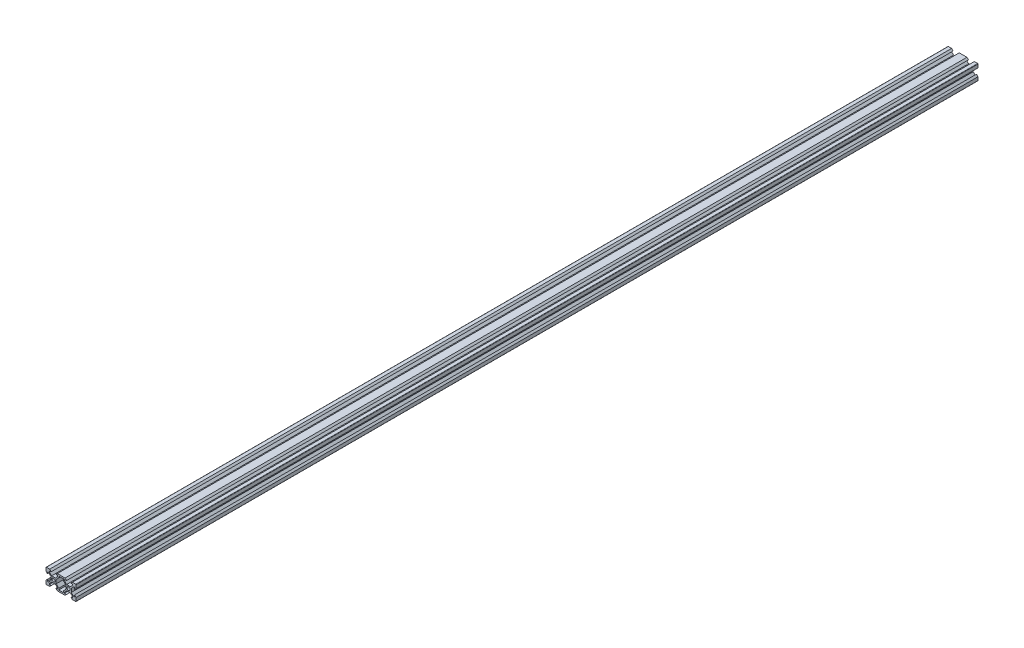
SolidWorks part; units mm, degrees
material "6063-T5"
ref_plane "Front Plane" through (0, 0, 0) normal (0, 0, 1) x (1, 0, 0)
ref_plane "Top Plane" through (0, 0, 0) normal (0, 1, 0) x (1, 0, 0)
ref_plane "Right Plane" through (0, 0, 0) normal (1, 0, 0) x (0, 0, -1)
sketch "Sketch1" plane through (0, 0, 0) normal (0, 0, 1) x (1, 0, 0)
  line L0 (-26.1395, 0) -> (11.0607, 0) construction
  line L1 (0, -20.0817) -> (0, 17.1243) construction
  line L2 (-20, 10.7318) -> (-20, -11.6858) construction
  line L3 (20, 11.8444) -> (20, -11.2237) construction
  line L4 (-23.1467, 10) -> (24.2381, 10) construction
  line L5 (23.8217, -10) -> (-26.7834, -10) construction
  line L6 (3, -5.9393) -> (3, -8)
  line L7 (-20, -10) -> (-15.5, -10)
  line L8 (-20, -10) -> (-20, -5.5)
  line L9 (-18, -5.5) -> (-16.5607, -5.5)
  line L10 (-15.5, -8) -> (-15.5, -6.5607)
  line L11 (-20, 10) -> (-15.5, 10)
  line L12 (-20, 10) -> (-20, 5.5)
  line L13 (-18, 5.5) -> (-16.5607, 5.5)
  line L14 (-15.5, 8) -> (-15.5, 6.5607)
  line L15 (20, 10) -> (15.5, 10)
  line L16 (20, 10) -> (20, 5.5)
  line L17 (18, 5.5) -> (16.5607, 5.5)
  line L18 (15.5, 8) -> (15.5, 6.5607)
  line L19 (20, -10) -> (15.5, -10)
  line L20 (20, -10) -> (20, -5.5)
  line L21 (18, -5.5) -> (16.5607, -5.5)
  line L22 (15.5, -8) -> (15.5, -6.5607)
  line L23 (4.5, -6.5607) -> (4.5, -8)
  line L24 (12.5393, 3.6) -> (15.5, 6.5607)
  line L25 (7.4607, -3.6) -> (4.5, -6.5607)
  line L27 (-4.5, 8) -> (-6.9, 8)
  line L28 (-12.5393, -3.6) -> (-15.5, -6.5607)
  line L29 (7.4607, 3.6) -> (4.5, 6.5607)
  line L30 (12.5393, -3.6) -> (15.5, -6.5607)
  line L31 (-13.6, -2.5393) -> (-16.5607, -5.5)
  line L32 (-13.6, 2.5393) -> (-16.5607, 5.5)
  line L33 (6.4, -2.5393) -> (3, -5.9393)
  line L34 (20, 5.5) -> (20, 5.1)
  line L35 (20, 5.1) -> (18, 3.1)
  line L36 (18, 3.1) -> (18, 5.5)
  line L37 (20, -5.5) -> (20, -5.1)
  line L38 (20, -5.1) -> (18, -3.1)
  line L39 (18, -3.1) -> (18, -5.5)
  line L40 (15.5, 10) -> (15.1, 10)
  line L41 (15.1, 10) -> (13.1, 8)
  line L42 (13.1, 8) -> (15.5, 8)
  line L43 (15.5, -10) -> (15.1, -10)
  line L44 (15.1, -10) -> (13.5138, -8)
  line L45 (13.5138, -8) -> (15.5, -8)
  line L46 (-15.5, 10) -> (-15.1, 10)
  line L47 (-15.1, 10) -> (-13.1, 8)
  line L48 (-13.1, 8) -> (-15.5, 8)
  line L49 (-20, 5.5) -> (-20, 5.1)
  line L50 (-20, 5.1) -> (-18, 3.1)
  line L51 (-18, 3.1) -> (-18, 5.5)
  line L52 (-20, -5.5) -> (-20, -5.1)
  line L53 (-20, -5.1) -> (-18, -3.1)
  line L54 (-18, -3.1) -> (-18, -5.5)
  line L55 (-15.5, -10) -> (-15.1, -10)
  line L56 (-15.1, -10) -> (-13.1, -8)
  line L57 (-13.1, -8) -> (-15.5, -8)
  line L58 (6.4, 2.5393) -> (3, 5.9393)
  line L59 (3, 8) -> (-3, 8)
  line L61 (-3, 5.9393) -> (-3, 8)
  line L62 (-12.5393, 3.6) -> (-15.5, 6.5607)
  line L63 (-4.5, 6.5607) -> (-4.5, 8)
  line L64 (4.5, 6.5607) -> (4.5, 8)
  line L65 (3, 5.9393) -> (3, 8)
  line L66 (13.6, 2.5393) -> (16.5607, 5.5)
  line L67 (12.1, 0) -> (30.0509, 0) construction
  line L68 (-7.4607, 3.6) -> (-4.5, 6.5607)
  line L69 (3, -8) -> (-3, -8)
  line L70 (-6.4, 2.5393) -> (-3, 5.9393)
  line L71 (13.6, -2.5393) -> (16.5607, -5.5)
  line L73 (-3, -5.9393) -> (-3, -8)
  line L74 (-4.5, -6.5607) -> (-4.5, -8)
  line L75 (-7.4607, -3.6) -> (-4.5, -6.5607)
  line L76 (-6.4, -2.5393) -> (-3, -5.9393)
  line L77 (5.3138, -10) -> (7.3138, -8)
  line L78 (7.3138, -8) -> (4.5, -8)
  line L79 (-6.9, -8) -> (-4.9, -10)
  line L80 (-4.9, -10) -> (5.3138, -10)
  line L81 (5.3138, 10) -> (7.3138, 8)
  line L82 (-4.9, 10) -> (5.3138, 10)
  line L83 (-6.9, 8) -> (-4.9, 10)
  line L84 (7.3138, 8) -> (4.5, 8)
  line L85 (7.4607, -3.6) -> (12.5393, -3.6)
  line L86 (-7.4607, -3.6) -> (-12.5393, -3.6)
  line L87 (-6.4, -2.5393) -> (-6.4, 2.5393)
  line L88 (-7.4607, 3.6) -> (-12.5393, 3.6)
  line L89 (-13.6, -2.5393) -> (-13.6, 2.5393)
  line L90 (6.4, -2.5393) -> (6.4, 2.5393)
  line L91 (13.6, -2.5393) -> (13.6, 2.5393)
  line L92 (7.4607, 3.6) -> (12.5393, 3.6)
  line L93 (-4.5, -8) -> (-6.9, -8)
  circle A0 centre (-10, 0) radius 2.1
  circle A1 centre (10, 0) radius 2.1
  dimension "D2" = 4.2
  dimension "D5" = 45
  dimension "D6" = 45
  dimension "D7" = 6.2
  dimension "D8" = 6.2
  dimension "D11" = 3.6
  dimension "D12" = 3.6
  dimension "D38" = 2.4
  dimension "D39" = 45
  dimension "D40" = 2.4
  dimension "D41" = 45
  dimension "D42" = 2
  dimension "D43" = 45
  dimension "D44" = 2.4
  dimension "D45" = 2
  dimension "D49" = 11
extrude "Boss-Extrude1" add sketch "Sketch1" along normal blind 1200
fillet "Fillet1" radius 0.5 4 edges at (-20, -10, 600) (-20, 10, 600) (20, -10, 600) (20, 10, 600)
